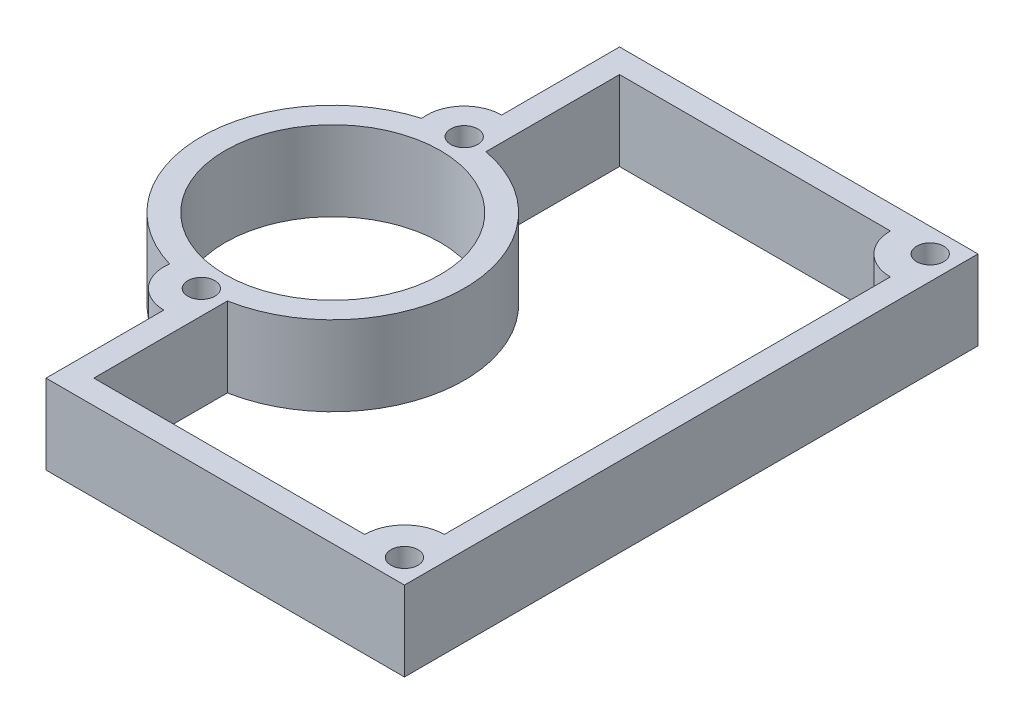
SolidWorks part; units mm, degrees
material "Acrylic (Medium-high impact)"
ref_plane "Front Plane" through (0, 0, 0) normal (0, 0, 1) x (1, 0, 0)
ref_plane "Top Plane" through (0, 0, 0) normal (0, 1, 0) x (1, 0, 0)
ref_plane "Right Plane" through (0, 0, 0) normal (1, 0, 0) x (0, 0, -1)
sketch "Sketch2" plane through (0, 0, 0) normal (0, 1, 0) x (1, 0, 0)
  line L0 (-55, 0) -> (55, 0) construction
  line L1 (0, 21.2) -> (0, 36)
  line L2 (0, 36) -> (45, 36)
  line L3 (45, -36) -> (45, 36)
  line L4 (0, -21.2) -> (0, -36)
  line L5 (0, -36) -> (45, -36)
  circle A0 centre (0, 0) radius 13.5
  arc A1 (-4.6521, 15.8306) -> (-4.6521, -15.8306) centre (0, 0) ccw
  arc A2 (-4.6521, 15.8306) -> (4.6521, 15.8306) centre (0, 16.5) cw
  circle A3 centre (0, 0) radius 16.5 construction
  arc A4 (-4.6521, -15.8306) -> (4.6521, -15.8306) centre (0, -16.5) ccw
  arc A5 (4.6521, -15.8306) -> (4.6521, 15.8306) centre (0, 0) ccw
  circle A6 centre (0, 16.5) radius 1.7
  circle A7 centre (0, -16.5) radius 1.7
  arc A8 (4.6521, 15.8306) -> (4.6521, -15.8306) centre (0, 0) ccw
  arc A9 (4.6521, 15.8306) -> (4.6521, -15.8306) centre (0, 0) cw
  arc A11 (4.6521, 15.8306) -> (4.6521, -15.8306) centre (0, 0) cw
  point P8 (45, 0)
  dimension "D1" = 27
  dimension "D2" = 3
  dimension "D3" = 3.4
  dimension "D4" = 3
  dimension "D5" = 72
  dimension "D6" = 45
extrude "Boss-Extrude2" add sketch "Sketch2" along normal blind 10 contours A8 A2 A6 | A7 A8 A5 A6 A1 A0 | A8 A7 A4 | A5 A4 L4 L5 L3 L2 L1 A2
sketch "Sketch3" plane through (0, 10, 0) normal (0, 1, 0) x (1, 0, 0)
  line L0 (3, 16.225) -> (3, 33)
  line L1 (3, 33) -> (42, 33)
  line L2 (42, 33) -> (42, -33)
  line L3 (42, -33) -> (3, -33)
  line L4 (3, -33) -> (3, -16.225)
  line L5 (0, 21.2) -> (0, 36) construction
  line L6 (0, 36) -> (45, 36) construction
  line L7 (45, -36) -> (45, 36) construction
  line L8 (0, -36) -> (45, -36) construction
  line L9 (0, -21.2) -> (0, -36) construction
  circle A0 centre (0, 0) radius 16.5 construction
  arc A1 (-4.6521, 15.8306) -> (-4.6521, -15.8306) centre (0, 0) ccw construction
  arc A2 (3, 16.225) -> (3, -16.225) centre (0, 0) cw
  dimension "D1" = 3
  dimension "D2" = 3
  dimension "D3" = 3
  dimension "D4" = 3
  dimension "D5" = 3
extrude "Cut-Extrude1" cut sketch "Sketch3" against normal through all
sketch "Sketch4" plane through (0, 10, 0) normal (0, 1, 0) x (1, 0, 0)
  line L1 (42, 33) -> (3, 33) construction
  line L2 (42, -33) -> (42, 33) construction
  line L3 (3, -33) -> (42, -33) construction
  line L4 (37, -33) -> (42, -33)
  line L5 (42, -33) -> (42, -28)
  line L6 (37, 33) -> (42, 33)
  line L7 (42, 33) -> (42, 28)
  arc A0 (37, 33) -> (42, 28) centre (42, 33) ccw
  arc A1 (37, -33) -> (42, -28) centre (42, -33) cw
  dimension "D1" = 5
  dimension "D2" = 5
extrude "Boss-Extrude3" add sketch "Sketch4" against normal through all
sketch "Sketch5" plane through (0, 10, 0) normal (0, 1, 0) x (1, 0, 0)
  circle A0 centre (42, 33) radius 1.7
  circle A1 centre (42, -33) radius 1.7
  arc A2 (42, -28) -> (37, -33) centre (42, -33) ccw construction
  arc A3 (37, 33) -> (42, 28) centre (42, 33) ccw construction
  dimension "D1" = 3.4
  dimension "D2" = 3.4
extrude "Cut-Extrude3" cut sketch "Sketch5" against normal through all
